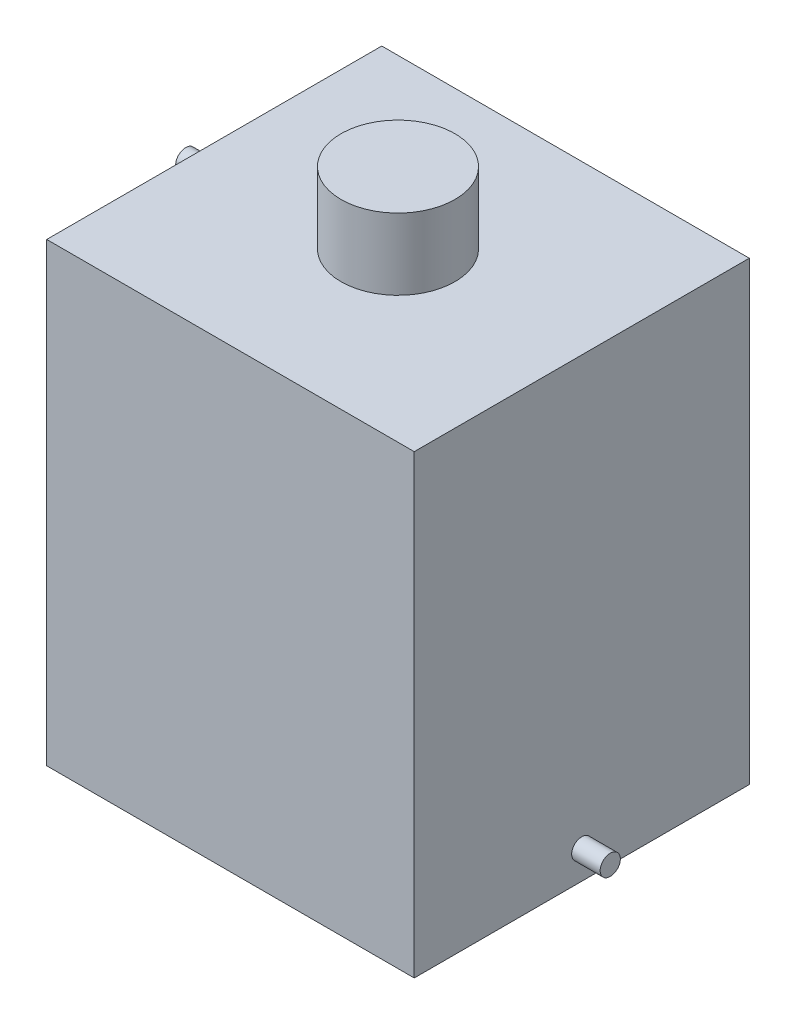
SolidWorks part; units mm, degrees
ref_plane "X-Y Datum" through (0, 0, 0) normal (0, 0, 1) x (1, 0, 0)
ref_plane "X-Z Datum" through (0, 0, 0) normal (0, 1, 0) x (1, 0, 0)
ref_plane "Y-Z Datum" through (0, 0, 0) normal (1, 0, 0) x (0, 0, -1)
sketch "Sketch1" plane through (0, 0, 0) normal (0, 1, 0) x (1, 0, 0)
  line L1 (81.915, 74.676) -> (-81.915, 74.676)
  line L2 (81.915, 74.676) -> (81.915, -74.676)
  line L3 (81.915, -74.676) -> (-81.915, -74.676)
  line L4 (-81.915, 74.676) -> (-81.915, -74.676)
  line L5 (81.915, 74.676) -> (-81.915, -74.676) construction
  line L6 (81.915, -74.676) -> (-81.915, 74.676) construction
  point P0 (0, 0)
  dimension "D1" = 163.83
  dimension "D2" = 149.352
extrude "Boss-Extrude1" add sketch "Sketch1" along normal blind 203.2
sketch "Sketch2" plane through (0, 203.2, 0) normal (0, 1, 0) x (1, 0, 0)
  circle A0 centre (0, 0) radius 25.4
  dimension "D1" = 50.8
extrude "Boss-Extrude2" add sketch "Sketch2" along normal blind 31.75
sketch "Sketch3" plane through (-81.915, 0, 0) normal (-1, 0, 0) x (0, 0, 1)
  line L0 (-74.676, 203.2) -> (74.676, 203.2) construction
  line L1 (-74.676, 203.2) -> (74.676, 203.2) construction
  line L2 (0, 203.2) -> (0, 0) construction
  line L3 (-74.676, 0) -> (74.676, 0) construction
  circle A0 centre (0, 190.5) radius 4.5
  dimension "D2" = 9
  dimension "D1" = 12.7
extrude "Boss-Extrude3" add sketch "Sketch3" along normal blind 12.7
sketch "Sketch5" plane through (81.915, 0, 0) normal (1, 0, 0) x (0, 0, -1)
  line L0 (-74.676, 0) -> (74.676, 0) construction
  line L1 (-74.676, 0) -> (74.676, 0) construction
  line L2 (0, 0) -> (0, 203.2) construction
  line L3 (-74.676, 203.2) -> (74.676, 203.2) construction
  circle A0 centre (0, 12.7) radius 4.5
  dimension "D1" = 9
  dimension "D2" = 12.7
extrude "Boss-Extrude4" add sketch "Sketch5" along normal blind 12.7
